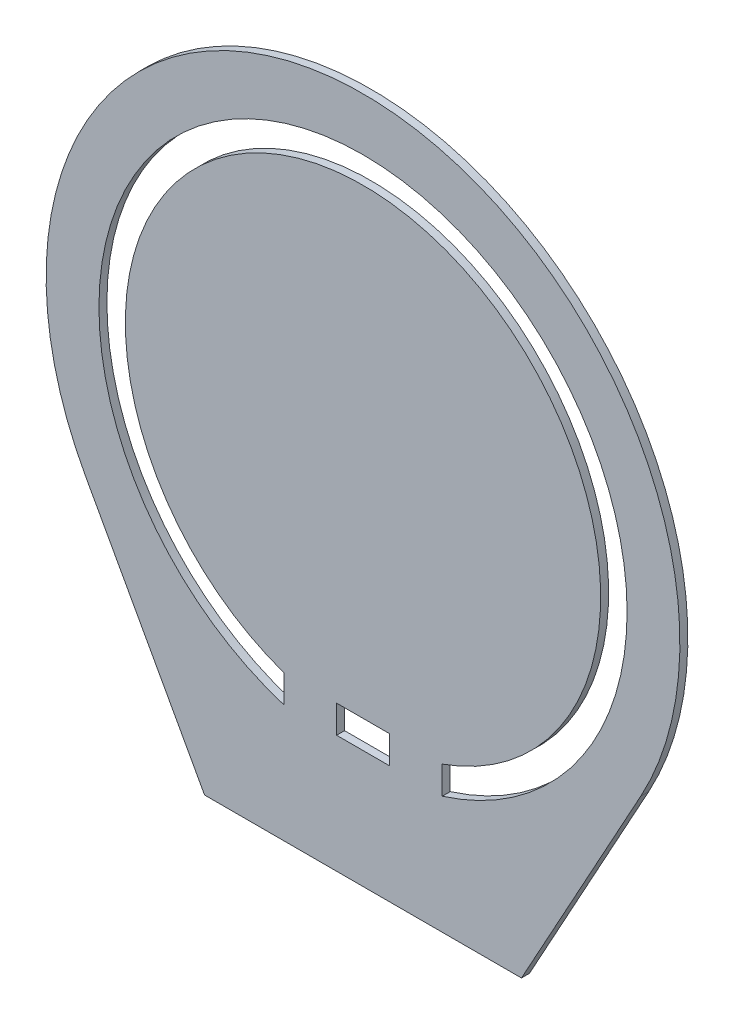
SolidWorks part; units mm, degrees
ref_plane "Plano frontal" through (0, 0, 0) normal (0, 0, 1) x (1, 0, 0)
ref_plane "Plano superior" through (0, 0, 0) normal (0, 1, 0) x (1, 0, 0)
ref_plane "Plano direito" through (0, 0, 0) normal (1, 0, 0) x (0, 0, -1)
sketch "Sketch1" plane through (0, 0, 0) normal (0, 0, 1) x (1, 0, 0)
  line L0 (-15, -35) -> (-7.5, -35)
  line L1 (-15, -35) -> (15, -35)
  line L4 (-15, -35) -> (-7.5, -35)
  line L5 (-7.5, -35) -> (-7.5, -23.8485)
  line L6 (-2.5, -23.8485) -> (2.5, -23.8485)
  line L7 (15, -35) -> (26.2929, -14.4459)
  line L8 (-2.5, -23.8485) -> (-2.5, -22.3607)
  line L9 (-7.5, -23.8485) -> (-7.5, -21.2132)
  line L10 (-2.5, -23.8485) -> (2.5, -23.8485)
  line L11 (2.5, -23.8485) -> (2.5, -22.3607)
  line L12 (7.5, -23.8485) -> (7.5, -21.2132)
  line L13 (2.5, -21.2132) -> (-2.5, -21.2132)
  line L14 (-2.5, -22.3607) -> (-2.5, -21.2132)
  line L15 (2.5, -22.3607) -> (2.5, -21.2132)
  line L16 (-15, -35) -> (-26.2929, -14.4459)
  arc A0 (7.5, -21.2132) -> (-7.5, -21.2132) centre (0, 0) ccw
  arc A1 (7.5, -23.8485) -> (-7.5, -23.8485) centre (0, 0) ccw
  arc A2 (26.2929, -14.4459) -> (-26.2929, -14.4459) centre (0, 0) ccw
  point P10 (0, -35)
  dimension "D1" = 45
  dimension "D2" = 50
  dimension "D3" = 60
  dimension "D4" = 5
  dimension "D5" = 30
  dimension "D6" = 7.5
  dimension "D7" = 5
  dimension "D8" = 2.6353
extrude "Boss-Extrude1" add sketch "Sketch1" along normal blind 0.7544
